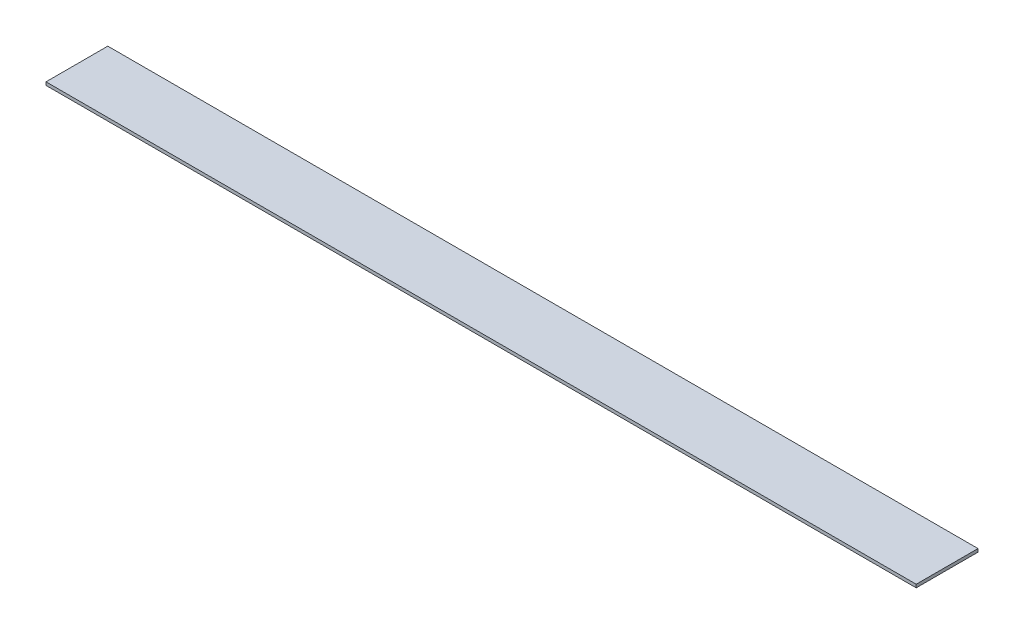
SolidWorks part; units mm, degrees
material "PET"
ref_plane "Спереди" through (0, 0, 0) normal (0, 0, 1) x (1, 0, 0)
ref_plane "Сверху" through (0, 0, 0) normal (0, 1, 0) x (1, 0, 0)
ref_plane "Справа" through (0, 0, 0) normal (1, 0, 0) x (0, 0, -1)
sketch "Эскиз1" plane through (0, 0, 0) normal (0, 1, 0) x (1, 0, 0)
  line L1 (0, 0) -> (138, 0)
  line L2 (0, 0) -> (0, 9.8)
  line L3 (0, 9.8) -> (138, 9.8)
  line L4 (138, 0) -> (138, 9.8)
  dimension "D1" = 138
  dimension "D2" = 9.8
extrude "Бобышка-Вытянуть1" add sketch "Эскиз1" along normal blind 0.5
